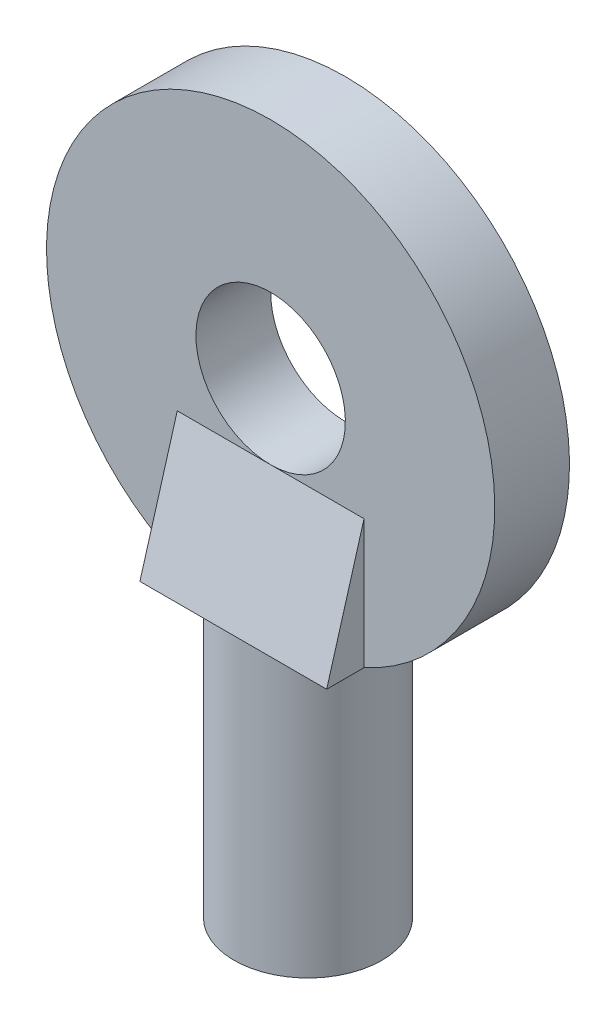
SolidWorks part; units mm, degrees
ref_plane "Front Plane" through (0, 0, 0) normal (0, 0, 1) x (1, 0, 0)
ref_plane "Top Plane" through (0, 0, 0) normal (0, 1, 0) x (1, 0, 0)
ref_plane "Right Plane" through (0, 0, 0) normal (1, 0, 0) x (0, 0, -1)
sketch "Sketch1" plane through (0, 0, 0) normal (0, 0, 1) x (1, 0, 0)
  line L0 (-6, 0) -> (6, 0) construction
  line L1 (0, 2) -> (0, -2)
  circle A0 centre (0, 0) radius 6
  circle A1 centre (0, 0) radius 2
  dimension "D1" = 12
  dimension "D2" = 4
extrude "Boss-Extrude1" add sketch "Sketch1" against normal blind 2 contours A0 L0 A1 | L0 A0 A1
sketch "Sketch2" plane through (0, 0, 0) normal (0, 0, 1) x (1, 0, 0)
  line L0 (0, -6) -> (0, -13) construction
  line L1 (-2.5, -13) -> (2.5, -13)
  line L2 (-2.5, -13) -> (-2.5, -5.4544)
  line L3 (2.5, -13) -> (2.5, -5.4544)
  line L4 (-2.5, -5.4544) -> (-2.5, -2)
  line L5 (-2.5, -2) -> (2.5, -2)
  line L6 (2.5, -2) -> (2.5, -5.4544)
  circle A0 centre (0, 0) radius 6 construction
  point P0 (0, 0)
  point P6 (0, -13)
  dimension "D2" = 5
extrude "Boss-Extrude3" add sketch "Sketch2" against normal blind 3 and the other way blind 1
sketch "Sketch3" plane through (0, -13, 0) normal (0, -1, 0) x (1, 0, 0)
  line L0 (-2.5, 1) -> (2.5, -3) construction
  line L1 (2.5, 1) -> (2.5, -3)
  line L2 (2.5, -3) -> (-2.5, -3)
  line L3 (-2.5, -3) -> (-2.5, 1)
  line L4 (-2.5, 1) -> (2.5, 1)
  circle A0 centre (0, -1) radius 1.9801
extrude "Cut-Extrude1" cut sketch "Sketch3" against normal up to vertex (7.5456 mm away)
sketch "Sketch5" plane through (2.5, 0, 0) normal (1, 0, 0) x (0, 0, -1)
  line L0 (-1, -5.4544) -> (0, -2)
  line L1 (3, -5.4544) -> (2, -2)
  line L2 (0, -2) -> (-1, -2)
  line L3 (-1, -2) -> (0, -2) construction
  line L4 (-1, -2) -> (-1, -5.4544)
  line L5 (2, -2) -> (3, -2)
  line L6 (3, -2) -> (3, -5.4544)
extrude "Cut-Extrude2" cut sketch "Sketch5" against normal blind 8
sketch "Sketch6" plane through (0, -13, 0) normal (0, -1, 0) x (1, 0, 0)
  line L0 (0, -1) -> (0.4, -1) construction
  circle A0 centre (0, -1) radius 0.4
  dimension "D1" = 0.4
extrude "Cut-Extrude3" cut sketch "Sketch6" against normal blind 4
